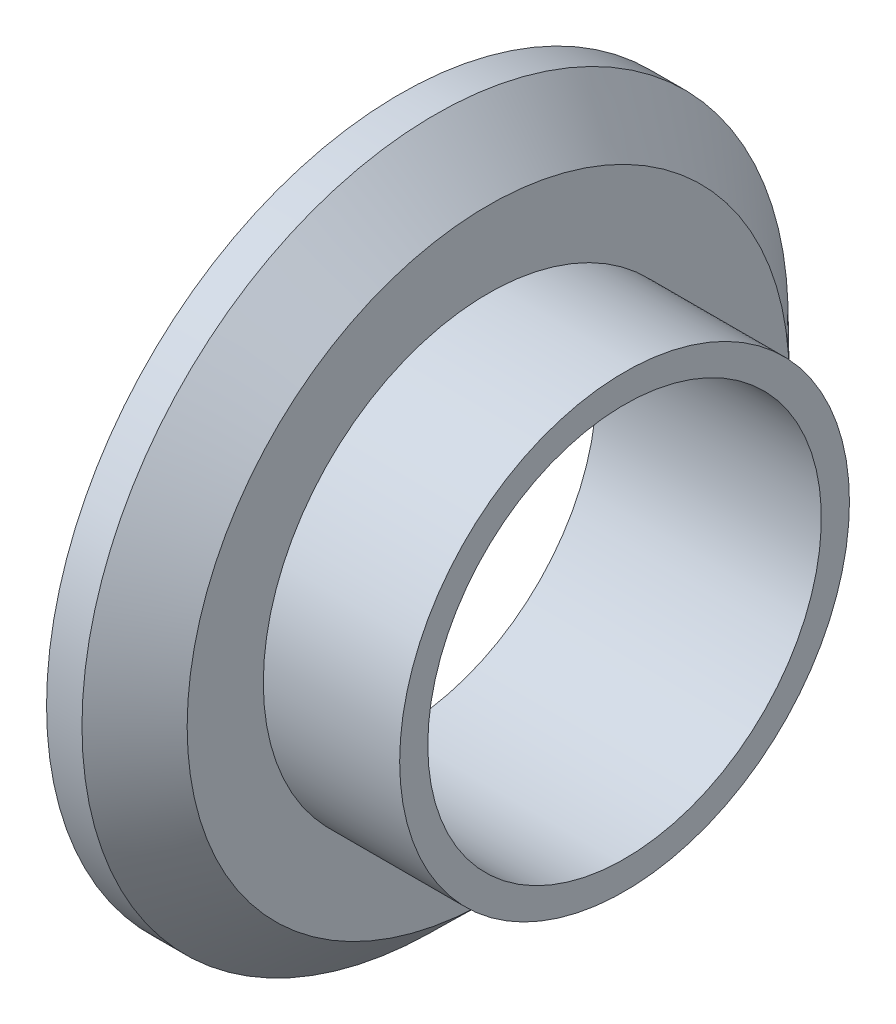
SolidWorks part; units mm, degrees
ref_plane "Front Plane" through (0, 0, 0) normal (0, 0, 1) x (1, 0, 0)
ref_plane "Top Plane" through (0, 0, 0) normal (0, 1, 0) x (1, 0, 0)
ref_plane "Right Plane" through (0, 0, 0) normal (1, 0, 0) x (0, 0, -1)
sketch "Axial profile (mm)" plane through (0, 0, 0) normal (0, 0, 1) x (1, 0, 0)
  line L0 (-110, 0) -> (75, 0) construction
  line L1 (1, 11.1125) -> (13.7, 11.1125)
  line L2 (13.7, 11.1125) -> (13.7, 12.7)
  line L3 (13.7, 12.7) -> (6, 12.7)
  line L4 (6, 12.7) -> (6, 17)
  line L5 (6, 17) -> (3, 19.94)
  line L6 (3, 19.94) -> (1, 19.94)
  line L7 (1, 19.94) -> (1, 11.1125)
revolve "Full revolution" add sketch "Axial profile (mm)" angle 360 about L0
